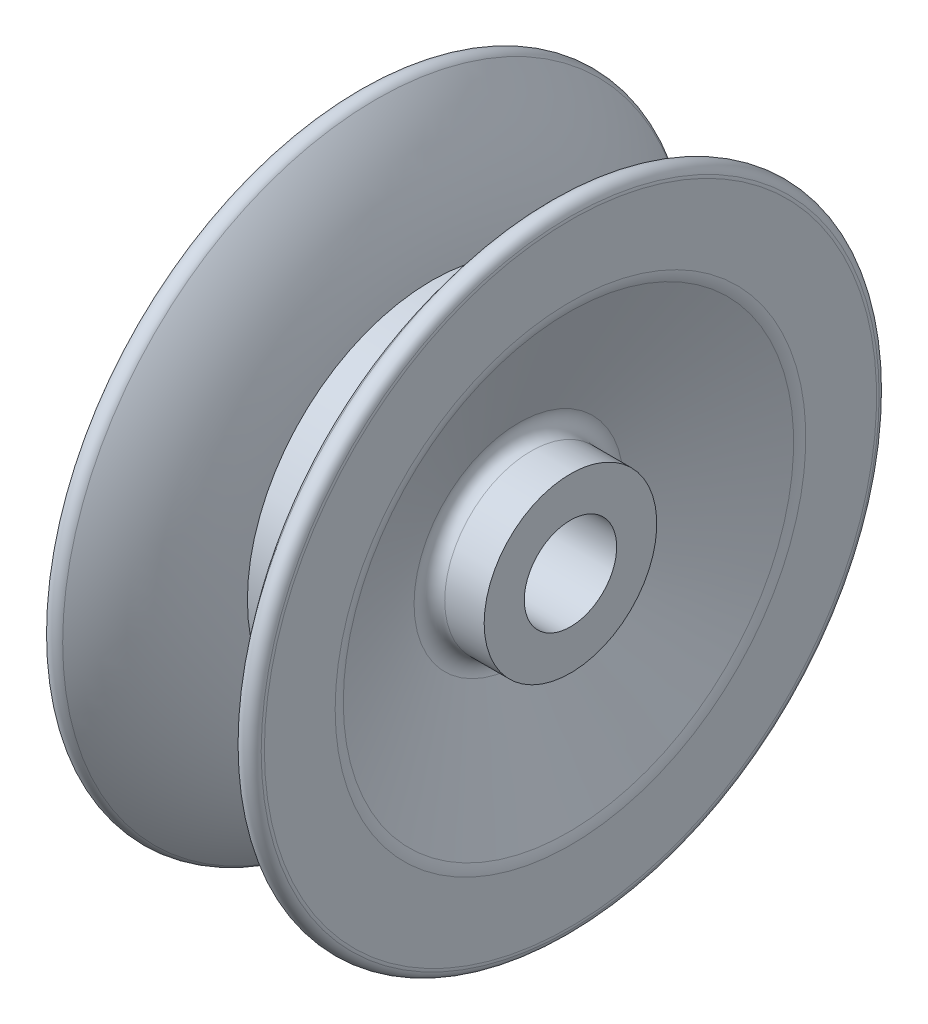
SolidWorks part; units mm, degrees
ref_plane "Front Plane" through (0, 0, 0) normal (0, 0, 1) x (1, 0, 0)
ref_plane "Top Plane" through (0, 0, 0) normal (0, 1, 0) x (1, 0, 0)
ref_plane "Right Plane" through (0, 0, 0) normal (1, 0, 0) x (0, 0, -1)
sketch "Sketch1" plane through (0, 0, 0) normal (0, 0, 1) x (1, 0, 0)
  line L0 (-18.5424, 21.9704) -> (32.2576, 21.9704) construction
  line L1 (-18.5454, -51.0546) -> (-18.5454, -34.1699)
  line L2 (-18.5454, 1.3805) -> (-18.5454, 10.9478)
  line L3 (-6.2043, -3.0056) -> (-18.0652, -31.7476)
  line L4 (32.2546, -51.0546) -> (32.2546, -34.1699)
  line L5 (-18.5454, 10.9478) -> (32.2546, 10.9478)
  line L6 (6.8546, -54.2296) -> (6.8546, 98.1704) construction
  line L7 (-0.7923, -22.0573) -> (14.5015, -22.0573)
  line L10 (32.2546, 1.3805) -> (22.8485, 1.3805)
  line L11 (19.9136, -3.0056) -> (31.7745, -31.7476)
  line L12 (32.2546, 1.3805) -> (32.2546, 10.9478)
  line L14 (-18.5454, 1.3805) -> (-9.1393, 1.3805)
  arc A0 (27.7768, -52.8509) -> (14.5015, -22.0573) centre (70.0479, -16.3693) cw
  arc A1 (32.1802, -51.7382) -> (27.7768, -52.8509) centre (29.6997, -51.1913) cw
  arc A2 (22.8485, 1.3805) -> (19.9136, -3.0056) centre (22.8485, -1.7945) ccw
  arc A3 (31.7745, -31.7476) -> (32.2546, -34.1699) centre (25.9046, -34.1699) cw
  arc A4 (-9.1393, 1.3805) -> (-6.2043, -3.0056) centre (-9.1393, -1.7945) cw
  arc A5 (32.1802, -51.7382) -> (32.2546, -51.0546) centre (29.0796, -51.0546) ccw
  arc A6 (-18.4709, -51.7382) -> (-18.5454, -51.0546) centre (-15.3704, -51.0546) cw
  arc A7 (-18.0652, -31.7476) -> (-18.5454, -34.1699) centre (-12.1954, -34.1699) ccw
  arc A8 (-18.4709, -51.7382) -> (-14.0676, -52.8509) centre (-15.9905, -51.1913) ccw
  arc A9 (-14.0676, -52.8509) -> (-0.7923, -22.0573) centre (-56.3386, -16.3693) ccw
  point P0 (0, 0)
  point P16 (6.8546, -22.0573)
  point P17 (23.6494, -54.2296)
  point P39 (-9.9401, -54.2296)
  point P40 (6.8546, -22.0573)
  dimension "D2" = 2.54
  dimension "D3" = 3.175
  dimension "D4" = 6.35
  dimension "D1" = 3.175
revolve "Revolve1" add sketch "Sketch1" angle 360 about L0
